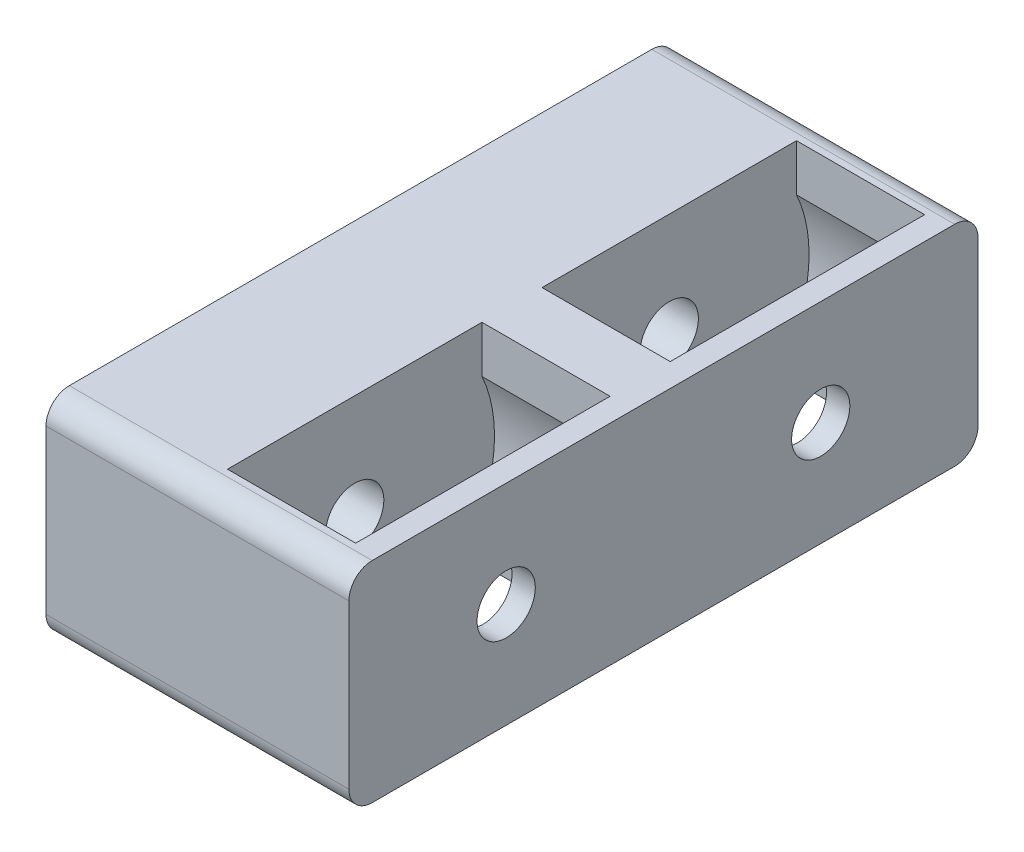
SolidWorks part; units mm, degrees
ref_plane "Front" through (0, 0, 0) normal (0, 0, 1) x (1, 0, 0)
ref_plane "Top" through (0, 0, 0) normal (0, 1, 0) x (1, 0, 0)
ref_plane "Right" through (0, 0, 0) normal (1, 0, 0) x (0, 0, -1)
sketch "Эскиз1" plane through (0, 0, 0) normal (1, 0, 0) x (0, 0, -1)
  line L0 (-13.5, 0) -> (13.5, 0) construction
  line L1 (-25, 9) -> (25, 9)
  line L2 (-27, 7) -> (-27, -7)
  line L3 (-25, -9) -> (25, -9)
  line L4 (27, 7) -> (27, -7)
  line L5 (-27, 9) -> (27, -9) construction
  line L6 (-27, -9) -> (27, 9) construction
  arc A0 (-27, -7) -> (-25, -9) centre (-25, -7) ccw
  arc A1 (25, -9) -> (27, -7) centre (25, -7) ccw
  arc A2 (25, 9) -> (27, 7) centre (25, 7) cw
  arc A3 (-25, 9) -> (-27, 7) centre (-25, 7) ccw
  circle A4 centre (-13.5, 0) radius 2.5
  circle A5 centre (13.5, 0) radius 2.5
  point P0 (0, 0)
  dimension "D3" = 2
  dimension "D1" = 54
  dimension "D2" = 18
  dimension "D4" = 27
extrude "Бобышка-Вытянуть1" add sketch "Эскиз1" along normal blind 24
sketch "Эскиз2" plane through (24, 0, 0) normal (1, 0, 0) x (0, 0, -1)
  line L0 (-24.4209, 9) -> (-24.4209, 4.9734)
  line L2 (-24.4209, -4.9734) -> (-24.4209, 4.9734) construction
  line L4 (24.4209, -4.9734) -> (24.4209, 4.9734) construction
  line L5 (24.4209, -4.9734) -> (24.4209, -9)
  line L6 (-2.5791, 4.9734) -> (-2.5791, 9)
  line L7 (25, 9) -> (-25, 9) construction
  line L8 (-25, -9) -> (25, -9) construction
  line L11 (24.4209, 9) -> (24.4209, 4.9734)
  line L14 (-24.4209, -4.9734) -> (-24.4209, -9)
  line L16 (2.5791, 9) -> (2.5791, 4.9734)
  line L17 (-2.5791, -4.9734) -> (-2.5791, -9)
  line L19 (2.5791, -9) -> (2.5791, -4.9734)
  line L20 (-2.5791, 9) -> (-24.4209, 9)
  line L21 (-24.4209, -9) -> (-2.5791, -9)
  line L22 (2.5791, -9) -> (24.4209, -9)
  line L23 (24.4209, 9) -> (2.5791, 9)
  arc A0 (-24.4209, 4.9734) -> (-24.4209, -4.9734) centre (-13.5, 0) ccw
  arc A1 (2.5791, 4.9734) -> (2.5791, -4.9734) centre (13.5, 0) ccw
  arc A2 (-2.5791, -4.9734) -> (-2.5791, 4.9734) centre (-13.5, 0) ccw
  arc A3 (24.4209, -4.9734) -> (24.4209, 4.9734) centre (13.5, 0) ccw
  point P6 (0, 0)
extrude "Вырез-Вытянуть1" cut sketch "Эскиз2" against normal blind 11
sketch "Эскиз3" plane through (24, 0, 0) normal (1, 0, 0) x (0, 0, -1)
  line B0 (-13.5, 0) -> (13.5, 0) construction
  line B1 (-25, 9) -> (25, 9)
  line B2 (-27, 7) -> (-27, -7)
  line B3 (-25, -9) -> (25, -9)
  line B4 (27, 7) -> (27, -7)
  line B5 (-27, 9) -> (27, -9) construction
  line B6 (-27, -9) -> (27, 9) construction
  arc B7 (-27, -7) -> (-25, -9) centre (-25, -7) ccw
  arc B8 (25, -9) -> (27, -7) centre (25, -7) ccw
  arc B9 (25, 9) -> (27, 7) centre (25, 7) cw
  arc B10 (-25, 9) -> (-27, 7) centre (-25, 7) ccw
  circle B11 centre (-13.5, 0) radius 2.5
  circle B12 centre (13.5, 0) radius 2.5
sketch_block_instance "Блок1-1"
sketch_block "Блок1" parameters "D2"=2, "D1"=54
extrude "Бобышка-Вытянуть2" add sketch "Эскиз3" along normal blind 2
